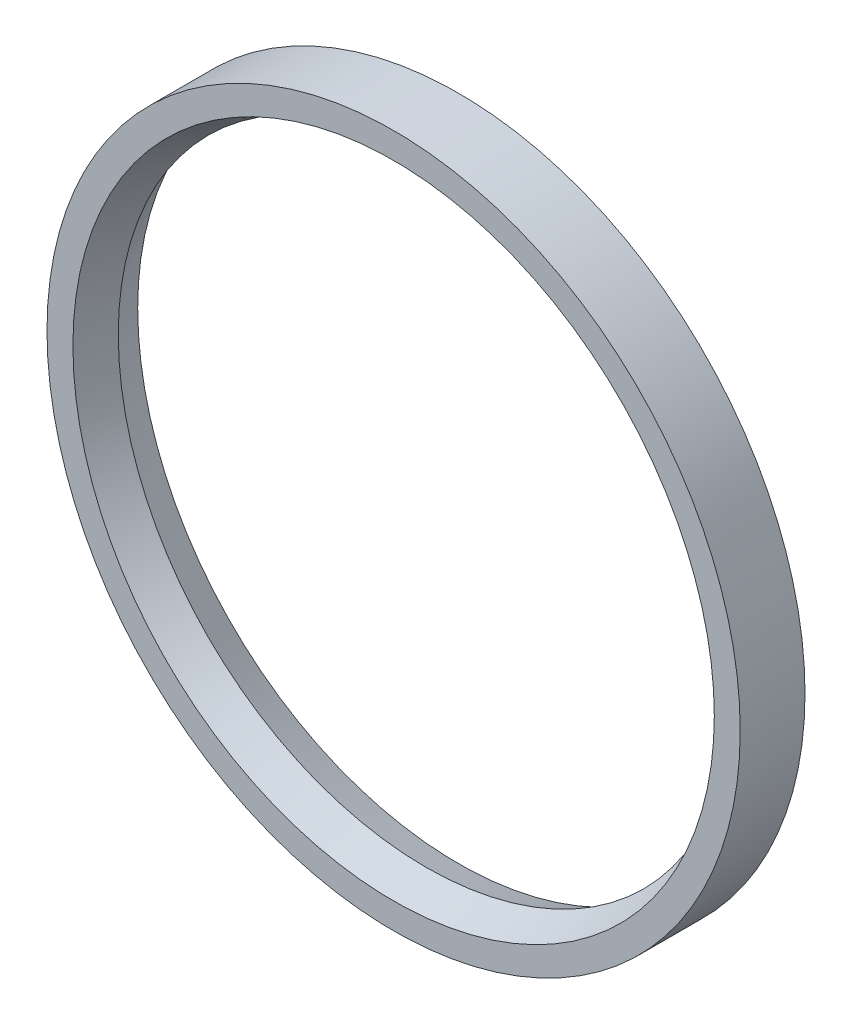
SolidWorks part; units mm, degrees
ref_plane "Front Plane" through (0, 0, 0) normal (0, 0, 1) x (1, 0, 0)
ref_plane "Top Plane" through (0, 0, 0) normal (0, 1, 0) x (1, 0, 0)
ref_plane "Right Plane" through (0, 0, 0) normal (1, 0, 0) x (0, 0, -1)
sketch "Sketch1" plane through (0, 0, 0) normal (1, 0, 0) x (0, 0, -1)
  line L0 (0, 0) -> (2.5, -1)
  line L1 (2.5, -1) -> (5, 0)
  line L2 (5, 0) -> (5, 2)
  line L3 (5, 2) -> (0, 2)
  line L4 (0, 2) -> (0, 0)
  line L5 (2.5, -1) -> (2.5, 2) construction
  line L6 (0, 0) -> (2.5, 0) construction
  line L7 (2.5, 0) -> (5, 0) construction
  line L8 (0, 0) -> (0, -24.75) construction
  line L9 (2.5, -1) -> (2.5, -24.75) construction
  line L10 (0, -24.75) -> (2.5, -24.75) construction
  point P6 (5.0624, -25)
  point P10 (5, 1.9281)
  dimension "D1" = 23.75
  dimension "D2" = 24.75
  dimension "D3" = 5
  dimension "D4" = 2
revolve "Revolve1" add sketch "Sketch1" angle 360 about L10
